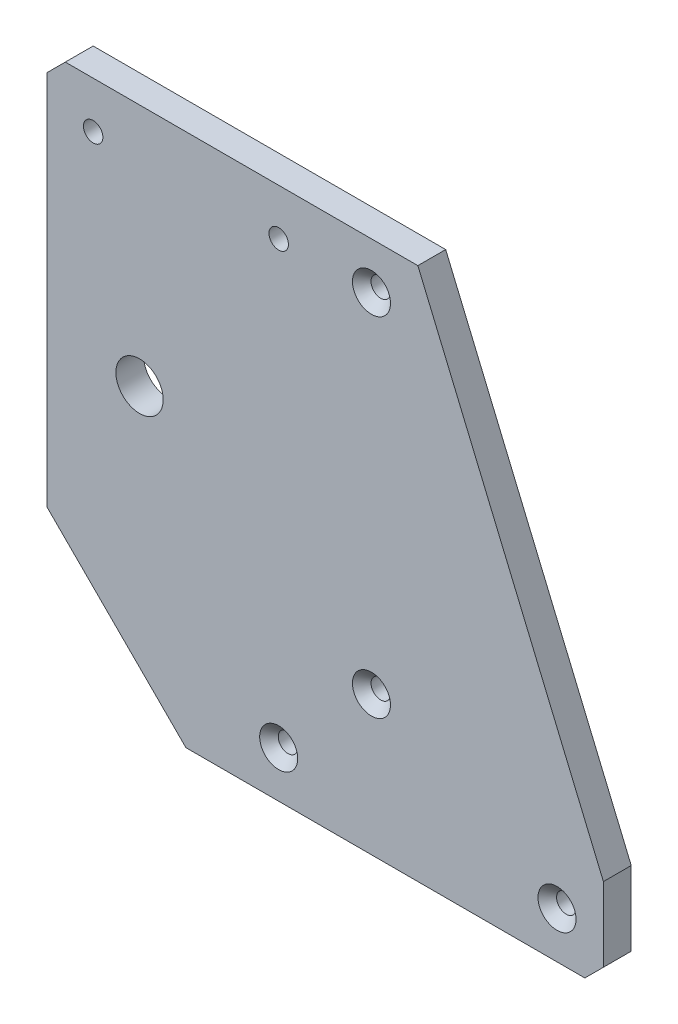
SolidWorks part; units mm, degrees
ref_plane "前视基准面" through (0, 0, 0) normal (0, 0, 1) x (1, 0, 0)
ref_plane "上视基准面" through (0, 0, 0) normal (0, 1, 0) x (1, 0, 0)
ref_plane "右视基准面" through (0, 0, 0) normal (1, 0, 0) x (0, 0, -1)
sketch "草图1" plane through (0, 0, 0) normal (0, 0, 1) x (1, 0, 0)
  line L0 (-20, 52.5) -> (-20, -62.5)
  line L1 (-20, -62.5) -> (100, -62.5)
  line L2 (100, -62.5) -> (100, -42.5)
  line L3 (100, -42.5) -> (60, 52.5)
  line L4 (60, 52.5) -> (-20, 52.5)
  circle A0 centre (0, 0) radius 5.1
  dimension "D1" = 62.5
  dimension "D2" = 10.2
  dimension "D3" = 52.5
  dimension "D4" = 20
  dimension "D5" = 20
  dimension "D6" = 80
  dimension "D7" = 40
extrude "凸台-拉伸1" add sketch "草图1" along normal mid plane 6
sketch "草图2" plane through (0, 0, 3) normal (0, 0, 1) x (1, 0, 0)
  line L0 (60, 52.5) -> (-20, 52.5) construction
  line L1 (-20, 52.5) -> (-20, -62.5) construction
  line L2 (50, 42.5) -> (50, -32.5) construction
  line L3 (30, -52.5) -> (90, -52.5) construction
  line L4 (-20, -62.5) -> (100, -62.5) construction
  line L5 (100, -62.5) -> (100, -42.5) construction
  circle A0 centre (-10, 42.5) radius 2.1
  circle A1 centre (30, 42.5) radius 2.1
  circle A2 centre (50, 42.5) radius 2.1
  circle A3 centre (50, -32.5) radius 2.1
  circle A4 centre (30, -52.5) radius 2.1
  circle A5 centre (90, -52.5) radius 2.1
  dimension "D1" = 4.2
  dimension "D2" = 10
  dimension "D3" = 10
  dimension "D4" = 40
  dimension "D5" = 10
  dimension "D8" = 10
  dimension "D9" = 20
  dimension "D6" = 10
  dimension "D7" = 20
extrude "切除-拉伸1" cut sketch "草图2" against normal through all
chamfer "倒角1" distance 30 angle 45 1 edges at (-20, -62.5, 0)
chamfer "倒角3" distance 4 angle 45 2 edges at (-20, 52.5, 0) (100, -62.5, 0)
chamfer "倒角2" distance 2 angle 45 4 edges at (52.1, 42.5, 3) (32.1, -52.5, 3) (52.1, -32.5, 3) (92.1, -52.5, 3)
